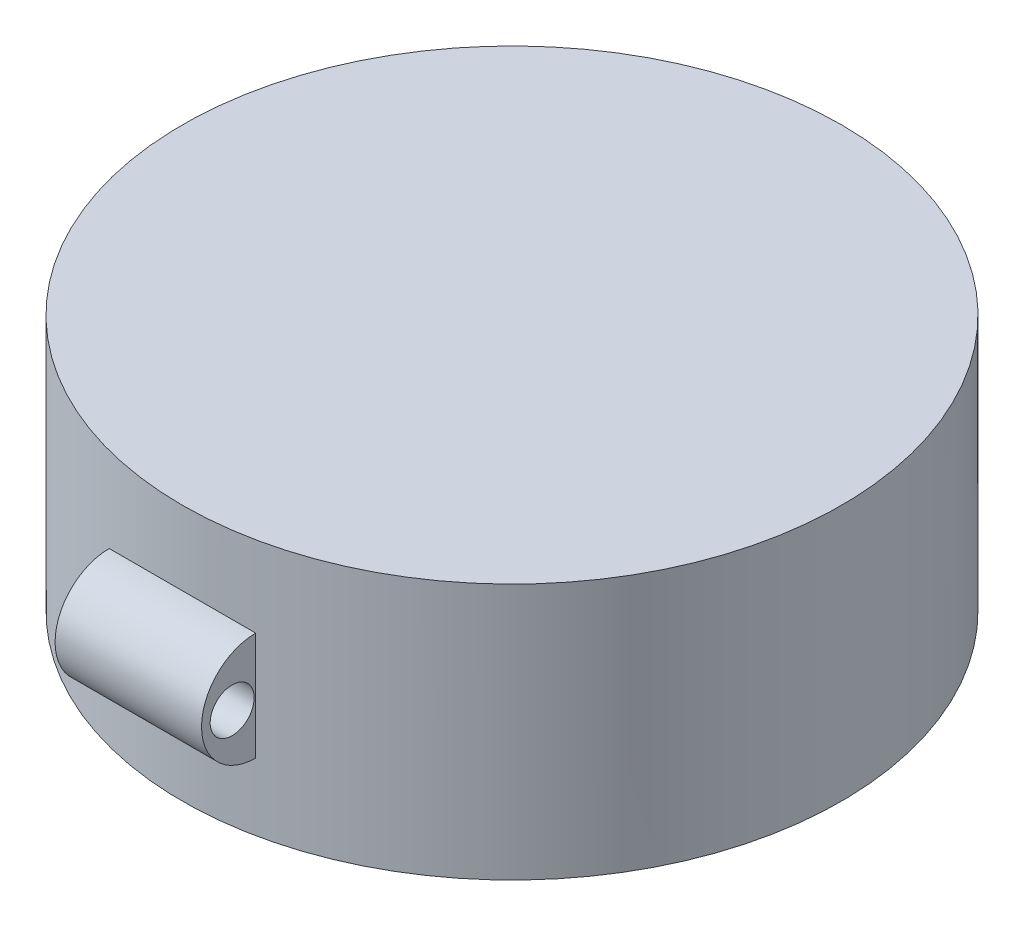
SolidWorks part; units mm, degrees
ref_plane "Front Plane" through (0, 0, 0) normal (0, 0, 1) x (1, 0, 0)
ref_plane "Top Plane" through (0, 0, 0) normal (0, 1, 0) x (1, 0, 0)
ref_plane "Right Plane" through (0, 0, 0) normal (1, 0, 0) x (0, 0, -1)
sketch "Sketch1" plane through (0, 0, 0) normal (0, 1, 0) x (1, 0, 0)
  circle A0 centre (0, 0) radius 45
  dimension "D1" = 90
extrude "Boss-Extrude1" add sketch "Sketch1" along normal blind 20
sketch "Sketch6" plane through (0, 0, 0) normal (0, 0, 1) x (1, 0, 0)
  line L1 (112.2918, -147.3486) -> (111.8592, -147.3486)
  line L2 (112.2918, -147.3486) -> (112.2918, -147.599)
  line L3 (112.2918, -147.599) -> (111.8592, -147.599)
  line L4 (111.8592, -147.3486) -> (111.8592, -147.599)
  point P4 (0, 0)
sketch "Sketch9" plane through (0, 0, 0) normal (0, -1, 0) x (1, 0, 0)
  circle A0 centre (0, 0) radius 45
extrude "Boss-Extrude3" add sketch "Sketch9" along normal blind 15
sketch "Sketch10" plane through (0, 0, 0) normal (1, 0, 0) x (0, 0, -1)
  line L0 (45, 9.8901) -> (45, -4.8901)
  line L1 (0, 86.5105) -> (0, -86.5105) construction
  line L2 (-45, 9.8901) -> (-45, -4.8901)
  arc A0 (45, -4.8901) -> (45, 9.8901) centre (45, 2.5) ccw
  arc A1 (-45, -4.8901) -> (-45, 9.8901) centre (-45, 2.5) cw
  circle A2 centre (48.7692, 2.5) radius 2.4532
extrude "Boss-Extrude4" add sketch "Sketch10" along normal mid plane 20 separate body contours A0 L0 | A1 L2
sketch "Sketch11" plane through (10, 0, 0) normal (1, 0, 0) x (0, 0, -1)
  line L0 (0, 86.5105) -> (0, -86.5105) construction
  circle A0 centre (-48.2069, 2.3674) radius 3.0046
  circle A1 centre (48.2069, 2.3674) radius 3.0046
extrude "Cut-Extrude1" cut sketch "Sketch11" against normal blind 20
